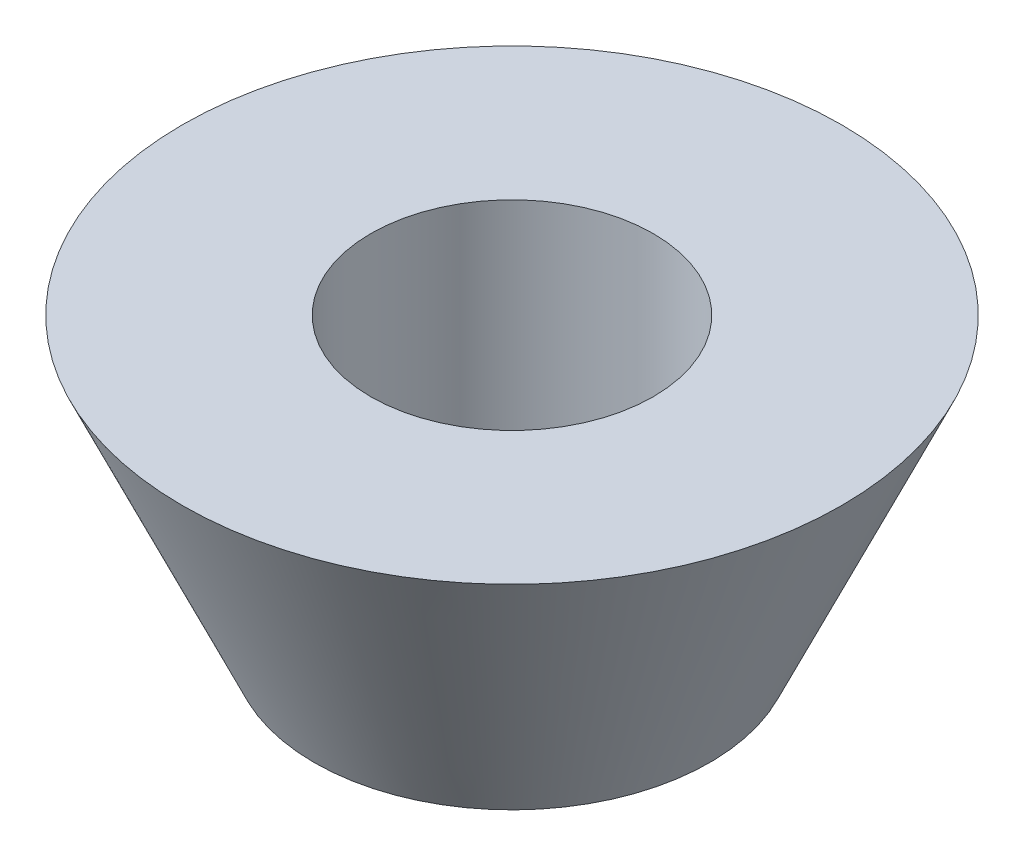
SolidWorks part; units mm, degrees
material "Alloy Steel"
ref_plane "X-Y Datum" through (0, 0, 0) normal (0, 0, 1) x (1, 0, 0)
ref_plane "X-Z Datum" through (0, 0, 0) normal (0, 1, 0) x (1, 0, 0)
ref_plane "Y-Z Datum" through (0, 0, 0) normal (1, 0, 0) x (0, 0, -1)
ref_axis "Axis1" through (0, 55, 0) along (0, -1, 0)
sketch "Sketch2" plane through (0, 0, 0) normal (0, 0, 1) x (1, 0, 0)
  line L0 (4.7625, 18.7723) -> (4.7625, 9.0454)
  line L1 (4.7625, 9.0454) -> (6.6675, 9.0454)
  line L2 (6.6675, 9.0454) -> (11.1125, 18.7723)
  line L3 (11.1125, 18.7723) -> (4.7625, 18.7723)
  line L4 (0, 55) -> (0, -31.0301) construction
  dimension "D1" = 4.7625
  dimension "D2" = 1.905
  dimension "D3" = 6.35
  dimension "D4" = 9.7269
revolve "Revolve1" add sketch "Sketch2" angle 360 about axis through (0, 55, 0) along (0, -1, 0)
